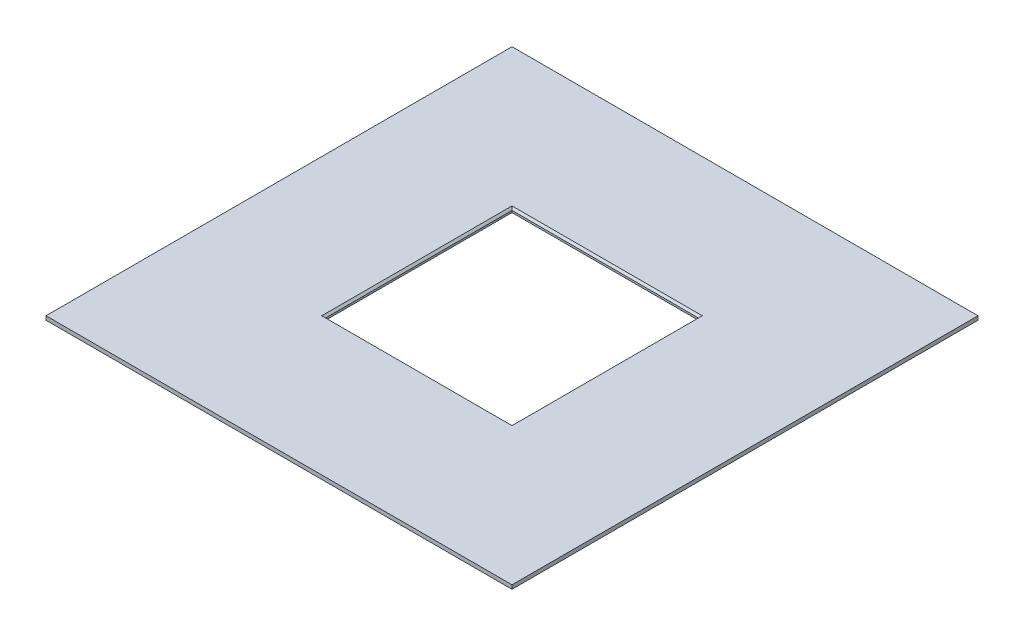
SolidWorks part; units mm, degrees
ref_plane "Front Plane" through (0, 0, 0) normal (0, 0, 1) x (1, 0, 0)
ref_plane "Top Plane" through (0, 0, 0) normal (0, 1, 0) x (1, 0, 0)
ref_plane "Right Plane" through (0, 0, 0) normal (1, 0, 0) x (0, 0, -1)
sketch "Sketch1" plane through (0, 0, 0) normal (0, 1, 0) x (1, 0, 0)
  line L1 (-60, 60) -> (60, 60)
  line L2 (-60, 60) -> (-60, -60)
  line L3 (-60, -60) -> (60, -60)
  line L4 (60, 60) -> (60, -60)
  line L5 (-60, 60) -> (60, -60) construction
  line L6 (-60, -60) -> (60, 60) construction
  line L7 (-24, 24) -> (24, 24)
  line L8 (-24, 24) -> (-24, -24)
  line L9 (-24, -24) -> (24, -24)
  line L10 (24, 24) -> (24, -24)
  line L11 (-24, 24) -> (24, -24) construction
  line L12 (-24, -24) -> (24, 24) construction
  point P0 (0, 0)
  point P6 (0, 0)
  dimension "D1" = 120
  dimension "D2" = 120
  dimension "D3" = 48
extrude "Boss-Extrude1" add sketch "Sketch1" along normal blind 1
chamfer "Chamfer1" distance 0.5 angle 45 4 edges at (24, 1, 0) (0, 1, 24) (-24, 1, 0) (0, 1, -24)
